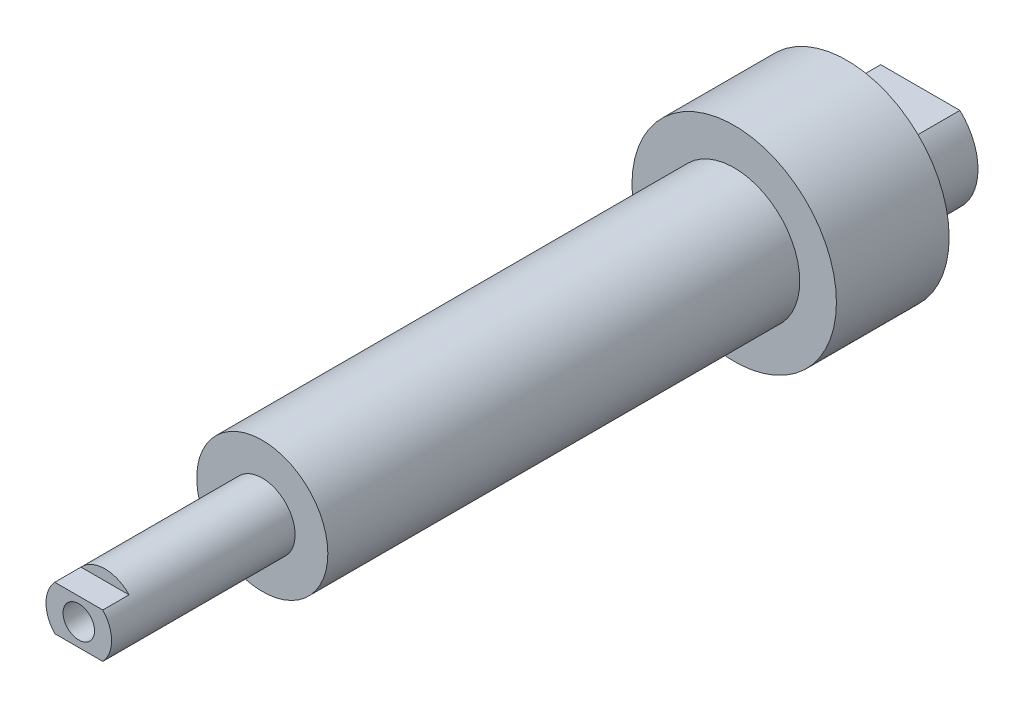
SolidWorks part; units mm, degrees
ref_plane "Front Plane" through (0, 0, 0) normal (0, 0, 1) x (1, 0, 0)
ref_plane "Top Plane" through (0, 0, 0) normal (0, 1, 0) x (1, 0, 0)
ref_plane "Right Plane" through (0, 0, 0) normal (1, 0, 0) x (0, 0, -1)
sketch "Sketch1" plane through (0, 0, 0) normal (0, 0, 1) x (1, 0, 0)
  circle A0 centre (0, 0) radius 39
  dimension "D1" = 78
extrude "Boss-Extrude1" add sketch "Sketch1" along normal blind 321
sketch "Sketch2" plane through (0, 0, 321) normal (0, 0, 1) x (1, 0, 0)
  circle A0 centre (0, 0) radius 25
  dimension "D1" = 50
extrude "Cut-Extrude1" cut sketch "Sketch2" against normal blind 250 flip side to cut
sketch "Sketch3" plane through (0, 0, 0) normal (0, 0, -1) x (-1, 0, 0)
  circle A0 centre (0, 0) radius 22
  dimension "D1" = 44
extrude "Cut-Extrude2" cut sketch "Sketch3" against normal blind 28 flip side to cut
sketch "Sketch4" plane through (0, 0, 0) normal (0, 0, -1) x (-1, 0, 0)
  circle A0 centre (0, 0) radius 13
  dimension "D1" = 26
extrude "Cut-Extrude3" cut sketch "Sketch4" against normal blind 91
sketch "Sketch5" plane through (0, 0, 0) normal (0, 0, -1) x (-1, 0, 0)
  line L0 (15.0997, -16) -> (-15.0997, -16)
  circle A0 centre (0, 0) radius 22 construction
  dimension "D1" = 16
extrude "Cut-Extrude4" cut sketch "Sketch5" against normal blind 25 and the other way through all
sketch "Sketch6" plane through (0, 0, 0) normal (0, 0, -1) x (-1, 0, 0)
  line L0 (15.0997, 16) -> (-15.0997, 16)
  arc A0 (15.0997, -16) -> (-15.0997, -16) centre (0, 0) ccw construction
  dimension "D1" = 16
extrude "Cut-Extrude5" cut sketch "Sketch6" against normal blind 25 and the other way through all flip side to cut
sketch "Sketch7" plane through (0, 0, 321) normal (0, 0, 1) x (1, 0, 0)
  circle A0 centre (0, 0) radius 12.5
  dimension "D1" = 25
extrude "Cut-Extrude6" cut sketch "Sketch7" against normal blind 70 flip side to cut
sketch "Sketch8" plane through (0, 0, 321) normal (0, 0, 1) x (1, 0, 0)
  line L0 (-9.1652, 8.5) -> (9.1652, 8.5)
  circle A0 centre (0, 0) radius 12.5 construction
  circle A1 centre (0, 0) radius 12.5 construction
  dimension "D1" = 8.5
extrude "Cut-Extrude7" cut sketch "Sketch8" against normal blind 10 and the other way through all
sketch "Sketch9" plane through (0, 0, 321) normal (0, 0, 1) x (1, 0, 0)
  line L0 (-9.1652, -8.5) -> (9.1652, -8.5)
  arc A0 (-9.1652, 8.5) -> (9.1652, 8.5) centre (0, 0) ccw construction
  dimension "D1" = 8.5
extrude "Cut-Extrude8" cut sketch "Sketch9" against normal blind 10 and the other way through all flip side to cut
sketch "Sketch10" plane through (0, 0, 321) normal (0, 0, 1) x (1, 0, 0)
  circle A0 centre (0, 0) radius 6
  dimension "D1" = 12
extrude "Cut-Extrude9" cut sketch "Sketch10" against normal through all
